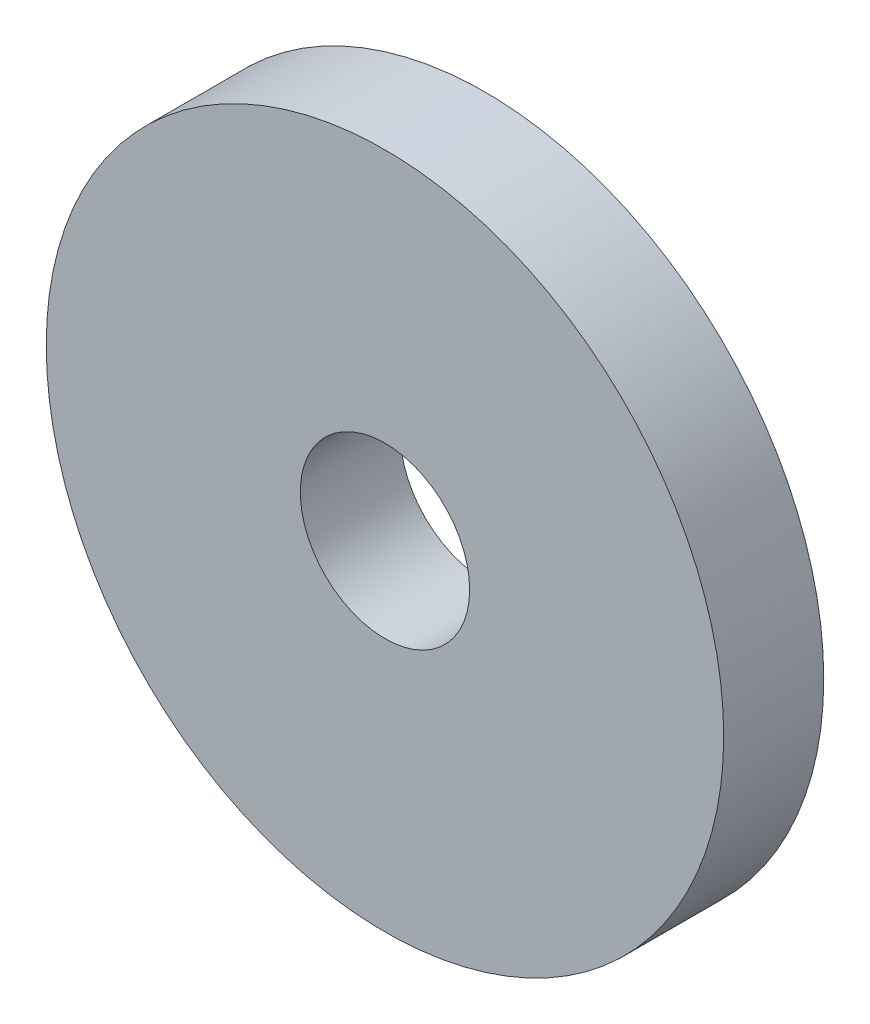
SolidWorks part; units mm, degrees
ref_plane "Front" through (0, 0, 0) normal (0, 0, 1) x (1, 0, 0)
ref_plane "Top" through (0, 0, 0) normal (0, 1, 0) x (1, 0, 0)
ref_plane "Right" through (0, 0, 0) normal (1, 0, 0) x (0, 0, -1)
sketch "草图1" plane through (0, 0, 0) normal (0, 0, 1) x (1, 0, 0)
  circle A0 centre (0, 0) radius 150
extrude "凸台-拉伸1" add sketch "草图1" along normal blind 29.5359
sketch "草图2" plane through (0, 0, 29.5359) normal (0, 0, 1) x (1, 0, 0)
  circle A0 centre (0, 0) radius 25
extrude "切除-拉伸2" cut sketch "草图2" against normal blind 29.5359
sketch "草图3" plane through (0, 0, 29.5359) normal (0, 0, 1) x (1, 0, 0)
  circle A0 centre (0, 0) radius 100
  circle A1 centre (0, 0) radius 150
extrude "切除-拉伸3" cut sketch "草图3" against normal blind 29.5359
